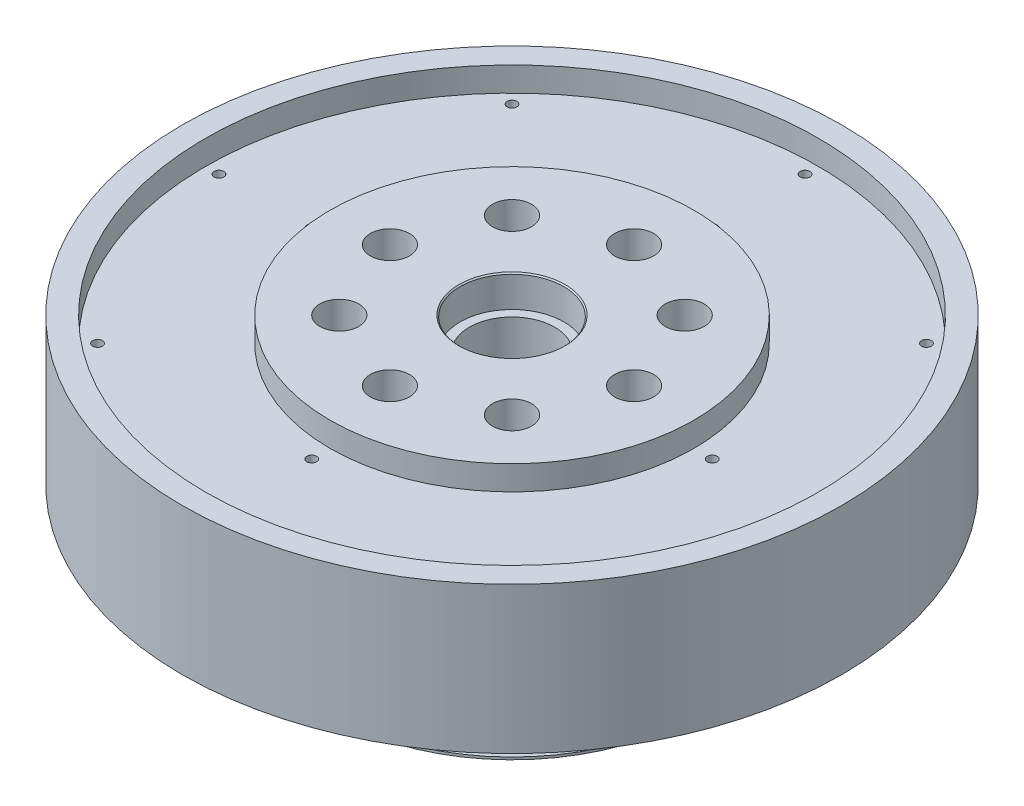
SolidWorks part; units mm, degrees
material "Ст 3 ГОСТ 380-88"
ref_plane "Front Plane" through (0, 0, 0) normal (0, 0, 1) x (1, 0, 0)
ref_plane "Top Plane" through (0, 0, 0) normal (0, 1, 0) x (1, 0, 0)
ref_plane "Right Plane" through (0, 0, 0) normal (1, 0, 0) x (0, 0, -1)
sketch "Sketch1" plane through (0, 0, 0) normal (1, 0, 0) x (0, 0, -1)
  line L0 (0, -14) -> (0, -31.7786) construction
  line L1 (-135, 60) -> (-135, 0)
  line L2 (-135, 0) -> (-125.5, 0)
  line L3 (-74.5, 0) -> (-74.5, -14)
  line L4 (-74.5, -14) -> (-20, -14)
  line L5 (-135, 60) -> (-125.5, 60)
  line L6 (0, 30.6711) -> (0, 60) construction
  line L7 (-17.5, 47) -> (-17.5, -11.5)
  line L8 (-17.5, -14) -> (0, -14) construction
  line L9 (0, 30.6711) -> (0, -14) construction
  line L10 (0, -14) -> (0, 30.6711) construction
  line L11 (-17.5, 60) -> (0, 60) construction
  line L12 (-20, 60) -> (-17.5, 57.5) construction
  line L13 (-20, -14) -> (-17.5, -11.5)
  line L14 (-21.25, 59.5) -> (-21.25, 47)
  line L15 (-21.25, 47) -> (-17.5, 47)
  line L16 (-21.25, 60) -> (-20, 60) construction
  line L17 (-17.5, 57.5) -> (-17.5, 47) construction
  line L18 (-21.75, 60) -> (-21.25, 59.5)
  line L19 (-125.5, 0) -> (-125.5, 10)
  line L20 (-125.5, 10) -> (-74.5, 10)
  line L21 (-74.5, 0) -> (-74.5, 10)
  line L22 (-125.5, 0) -> (-74.5, 0) construction
  line L23 (-125.5, 60) -> (-125.5, 50)
  line L24 (-125.5, 50) -> (-74.5, 50)
  line L25 (-74.5, 50) -> (-74.5, 60)
  line L26 (-125.5, 60) -> (-74.5, 60) construction
  line L27 (-74.5, 60) -> (-21.75, 60)
  dimension "D1" = 60
  dimension "D2" = 270
  dimension "D3" = 149
  dimension "D4" = 14
  dimension "D5" = 17.5
  dimension "D6" = 13
  dimension "D7" = 42.5
  dimension "D10" = 10
  dimension "D11" = 9.5
  dimension "D13" = 10
revolve "Revolve1" add sketch "Sketch1" angle 360 about L0
sketch "Sketch2" plane through (0, 60, 0) normal (0, 1, 0) x (1, 0, 0)
  line L0 (-50, 0) -> (0, 0) construction
  circle A0 centre (-50, 0) radius 4
  circle A1 centre (-35.3553, 35.3553) radius 4
  circle A2 centre (0, 50) radius 4
  circle A3 centre (35.3553, 35.3553) radius 4
  circle A4 centre (50, 0) radius 4
  circle A5 centre (35.3553, -35.3553) radius 4
  circle A6 centre (0, -50) radius 4
  circle A7 centre (-35.3553, -35.3553) radius 4
  point P21 (0, 0)
  dimension "D1" = 8
  dimension "D2" = 8
  dimension "D3" = 50
extrude "Cut-Extrude1" cut sketch "Sketch2" against normal through all both and the other way through all
sketch "Sketch3" plane through (0, 10, 0) normal (0, -1, 0) x (1, 0, 0)
  line L0 (0, 129.2853) -> (0, -136.9499) construction
  line L1 (0, 0) -> (0, 132.1781) construction
  line L2 (0, 0) -> (-104.479, 104.479) construction
  circle A0 centre (0, 82) radius 2
  circle A1 centre (0, 120) radius 2
  circle A2 centre (84.8528, 84.8528) radius 2
  circle A3 centre (57.9828, 57.9828) radius 2 construction
  circle A4 centre (120, 0) radius 2
  circle A5 centre (82, 0) radius 2
  circle A6 centre (84.8528, -84.8528) radius 2
  circle A7 centre (57.9828, -57.9828) radius 2 construction
  circle A8 centre (0, -120) radius 2
  circle A9 centre (0, -82) radius 2
  circle A10 centre (-84.8528, -84.8528) radius 2
  circle A11 centre (-57.9828, -57.9828) radius 2 construction
  circle A12 centre (-120, 0) radius 2
  circle A13 centre (-82, 0) radius 2
  circle A14 centre (-84.8528, 84.8528) radius 2
  circle A15 centre (-57.9828, 57.9828) radius 2 construction
  circle A16 centre (0, 0) radius 120 construction
  point P104 (0, 0)
  dimension "D1" = 4
  dimension "D4" = 120
  dimension "D3" = 240
  dimension "D2" = 82
  dimension "D6" = 45
  dimension "D5" = 8
extrude "Cut-Extrude2" cut sketch "Sketch3" against normal blind 15
ref_plane "Plane1" through (0, 30, 0) normal (0, -1, 0) x (-1, 0, 0)
mirror "Mirror1" about plane through (0, 30, 0) normal (0, -1, 0) of "Cut-Extrude2"
sketch "Sketch4" plane through (0, 60, 0) normal (0, 1, 0) x (1, 0, 0)
  circle A0 centre (0, 50) radius 8
  circle A1 centre (0, 0) radius 50 construction
  circle A2 centre (35.3553, 35.3553) radius 8
  circle A3 centre (50, 0) radius 8
  circle A4 centre (35.3553, -35.3553) radius 8
  circle A5 centre (0, -50) radius 8
  circle A6 centre (-35.3553, -35.3553) radius 8
  circle A7 centre (-50, 0) radius 8
  circle A8 centre (-35.3553, 35.3553) radius 8
  point P22 (0, 0)
  dimension "D1" = 16
  dimension "D2" = 8
extrude "Cut-Extrude3" cut sketch "Sketch4" against normal blind 12
sketch "Sketch5" plane through (0, -14, 0) normal (0, -1, 0) x (1, 0, 0)
  circle A0 centre (35.3553, -35.3553) radius 4 construction
  circle A1 centre (0, 0) radius 74.5
  circle A2 centre (0, 0) radius 74.5
  circle A3 centre (0, -50) radius 4 construction
  circle A4 centre (-35.3553, -35.3553) radius 4 construction
  circle A5 centre (-50, 0) radius 4 construction
  circle A6 centre (50, 0) radius 4 construction
  circle A7 centre (35.3553, 35.3553) radius 4 construction
  circle A8 centre (-35.3553, 35.3553) radius 4 construction
  circle A9 centre (0, 50) radius 4 construction
  circle A10 centre (35.3553, -35.3553) radius 4
  circle A11 centre (0, -50) radius 4
  circle A12 centre (-35.3553, -35.3553) radius 4
  circle A13 centre (-50, 0) radius 4
  circle A14 centre (50, 0) radius 4
  circle A15 centre (35.3553, 35.3553) radius 4
  circle A16 centre (-35.3553, 35.3553) radius 4
  circle A17 centre (0, 50) radius 4
  circle A18 centre (0, 0) radius 17.5 construction
  circle A19 centre (0, 0) radius 17.5
  dimension "D1" = 0
extrude "Boss-Extrude1" add sketch "Sketch5" along normal blind 1 from offset 30 separate body
sketch "Sketch6" plane through (0, -14, 0) normal (0, -1, 0) x (1, 0, 0)
  circle A1 centre (0, 0) radius 74.5
  circle A2 centre (0, 0) radius 74.5
  dimension "D1" = 0
extrude "Cut-Extrude4" [suppressed] cut sketch "Sketch6" against normal blind 2.5
chamfer "Chamfer1" [suppressed] distance 5 angle 60
chamfer "Chamfer2" [suppressed] distance 10 angle 30
